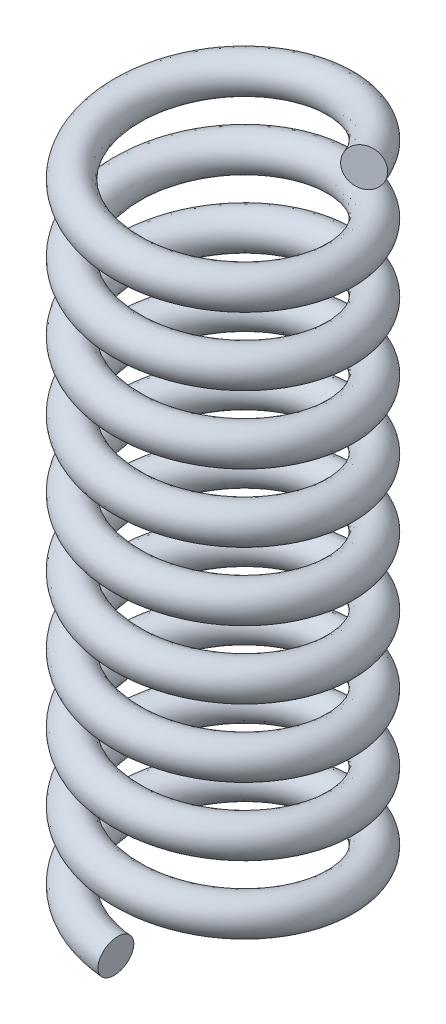
SolidWorks part; units mm, degrees
ref_plane "Front Plane" through (0, 0, 0) normal (0, 0, 1) x (1, 0, 0)
ref_plane "Top Plane" through (0, 0, 0) normal (0, 1, 0) x (1, 0, 0)
ref_plane "Right Plane" through (0, 0, 0) normal (1, 0, 0) x (0, 0, -1)
sketch "Sketch1" plane through (0, 0, 0) normal (0, 1, 0) x (1, 0, 0)
  circle A0 centre (0, 0) radius 30
  dimension "D1" = 60
curve "Helix/Spiral1" pitch 19 height 184 turns 9.6842
ref_plane "Plane1" through (0, 0, 30) normal (-0.995, 0.1003, 0) x (0, 0, 1)
sketch "Sketch2" plane through (0, 0, 30) normal (-0.995, 0.1003, 0) x (0, 0, 1)
  circle A0 centre (0, 0) radius 5
  dimension "D1" = 10
sweep "Sweep1" add profiles "Sketch2" path "Helix/Spiral1"
